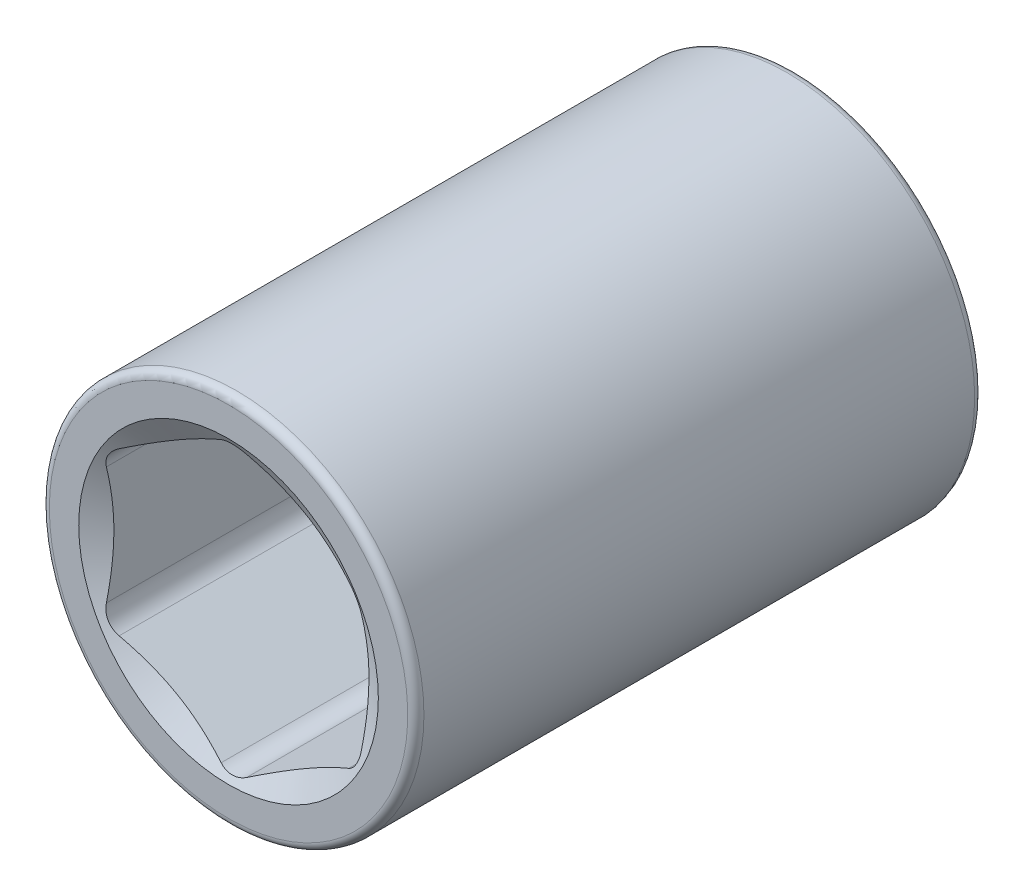
SolidWorks part; units mm, degrees
ref_plane "Front Plane" through (0, 0, 0) normal (0, 0, 1) x (1, 0, 0)
ref_plane "Top Plane" through (0, 0, 0) normal (0, 1, 0) x (1, 0, 0)
ref_plane "Right Plane" through (0, 0, 0) normal (1, 0, 0) x (0, 0, -1)
sketch "Sketch1" plane through (0, 0, 0) normal (1, 0, 0) x (0, 0, -1)
  line L0 (-11.1125, 0) -> (11.1125, 0) construction
  line L1 (11.1125, 3.175) -> (11.1125, -3.175) construction
  line L2 (-11.1125, 5) -> (-11.1125, -5) construction
  line L3 (-11.1125, 7.3422) -> (-11.1125, -7.3422) construction
  line L4 (-11.1125, 0) -> (-1.9844, 0) construction
  line L6 (11.1125, 7.3422) -> (11.1125, -7.3422) construction
  line L7 (-11.1125, 0) -> (2.7781, 0) construction
  line L9 (2.7781, 4) -> (2.7781, -4) construction
  dimension "Total Length" = 22.225
  dimension "Square Drive Size" = 6.35
  dimension "Size" = 10
  dimension "Diameter Nose End" = 14.6844
  dimension "Opening Depth" = 9.1281
  dimension "Diameter Drive End" = 14.6844
  dimension "Bolt Clearance" = 13.8906
  dimension "Bolt Clearance Diameter" = 8
sketch "Sketch4" plane through (0, 0, 0) normal (1, 0, 0) x (0, 0, -1)
  line L0 (-11.1125, 0) -> (-11.1125, 7.3422)
  line L2 (-11.1125, 7.3422) -> (11.1125, 7.3422)
  line L3 (-11.1125, 7.3422) -> (-11.1125, -7.3422) construction
  line L8 (11.1125, 3.175) -> (11.1125, -3.175) construction
  line L9 (11.1125, 7.3422) -> (11.1125, 0)
  line L11 (-11.1125, 0) -> (11.1125, 0)
revolve "Revolve1" add sketch "Sketch4" angle 360 about L11
sketch "Sketch5" plane through (0, 0, 11.1125) normal (0, 0, 1) x (1, 0, 0)
  line L27 (-5, 2.3094) -> (-5, -2.3094)
  line L28 (-4.5, -3.1754) -> (-0.5, -5.4848)
  line L29 (0.5, -5.4848) -> (4.5, -3.1754)
  line L30 (5, -2.3094) -> (5, 2.3094)
  line L31 (4.5, 3.1754) -> (0.5, 5.4848)
  line L32 (-0.5, 5.4848) -> (-4.5, 3.1754)
  circle A1 centre (0, 0) radius 5 construction
  arc A2 (-5, 2.3094) -> (-4.5, 3.1754) centre (-4, 2.3094) cw
  arc A3 (-5, -2.3094) -> (-4.5, -3.1754) centre (-4, -2.3094) ccw
  arc A4 (-0.5, -5.4848) -> (0.5, -5.4848) centre (0, -4.6188) ccw
  arc A5 (4.5, -3.1754) -> (5, -2.3094) centre (4, -2.3094) ccw
  arc A6 (5, 2.3094) -> (4.5, 3.1754) centre (4, 2.3094) ccw
  arc A7 (0.5, 5.4848) -> (-0.5, 5.4848) centre (0, 4.6188) ccw
  point P9 (0, 5.7735)
  point P21 (0, 5.7735)
  dimension "D2" = 1
  dimension "D1" = 10
extrude "Cut-Extrude1" cut sketch "Sketch5" against normal up to vertex (9.1281 mm away) up to point (0, 0, 1.9844)
sketch "Sketch7" plane through (0, 0, 1.9844) normal (0, 0, 1) x (1, 0, 0)
  circle A1 centre (0, 0) radius 4
  dimension "D1" = 8
extrude "Cut-Extrude3" cut sketch "Sketch7" against normal up to vertex (31.3974 mm away)
sketch "Sketch9" plane through (0, 0, -11.1125) normal (0, 0, -1) x (-1, 0, 0)
  line L6 (-3.175, -3.175) -> (3.175, -3.175)
  line L10 (-3.175, -3.175) -> (-3.175, 3.175)
  line L11 (-3.175, 3.175) -> (3.175, 3.175)
  line L12 (3.175, -3.175) -> (3.175, 3.175)
  line L13 (-3.175, -3.175) -> (3.175, 3.175) construction
  line L14 (-3.175, 3.175) -> (3.175, -3.175) construction
  point P0 (0, 0)
  dimension "D1" = 6.35
extrude "Cut-Extrude5" cut sketch "Sketch9" against normal up to vertex (8.3344 mm away) up to point (0, 0, -2.7781)
sketch "Sketch10" plane through (0, 0, -11.1125) normal (0, 0, -1) x (-1, 0, 0)
  line L0 (0, 0) -> (3.175, 3.175) construction
  line L1 (3.175, 3.175) -> (3.3546, 3.3546) construction
  circle A0 centre (0, 0) radius 4.7441
  dimension "D1" = 0.254
extrude "Cut-Extrude6" cut sketch "Sketch10" against normal through all draft 60
fillet "Fillet1" radius 0.3175 2 edges at (7.3422, 0, 11.1125) (7.3422, 0, -11.1125)
sketch "Sketch17" plane through (0, 0, 11.1125) normal (0, 0, 1) x (1, 0, 0)
  line L0 (0, 0) -> (0, 5.6188) construction
  line L1 (0, 5.6188) -> (0, 5.8728) construction
  circle A0 centre (0, 0) radius 5.8728
  arc A1 (0.5, 5.4848) -> (-0.5, 5.4848) centre (0, 4.6188) ccw construction
  dimension "D1" = 0.254
extrude "Cut-Extrude9" cut sketch "Sketch17" against normal through all draft 60
sketch "Sketch15" plane through (0, 0, 0) normal (1, 0, 0) x (0, 0, -1)
  line L15 (2.7781, -3.175) -> (10.9659, -3.175) construction
  line L18 (2.7781, 3.175) -> (10.9659, 3.175) construction
  line L19 (-1.9844, -4) -> (2.7781, -4) construction
  line L27 (2.7781, 4) -> (-1.9844, 4) construction
  line L29 (-10.9659, -5.6188) -> (-1.9844, -5.6188) construction
  line L31 (-1.9844, 5.6188) -> (-10.9659, 5.6188) construction
  line L32 (2.7781, -3.175) -> (10.9659, -3.175)
  line L33 (2.7781, 3.175) -> (10.9659, 3.175)
  line L34 (-1.9844, -4) -> (2.7781, -4)
  line L35 (2.7781, 4) -> (-1.9844, 4)
  line L36 (-10.9659, -5.6188) -> (-1.9844, -5.6188)
  line L38 (-1.9844, 5.6188) -> (-10.9659, 5.6188)
  line L39 (-1.9844, 5.6188) -> (-1.9844, -5.6188)
  line L40 (2.7781, 4) -> (2.7781, -4)
sketch "Sketch16" plane through (0, 0, 11.1125) normal (0, 0, 1) x (1, 0, 0)
  line L0 (-7.3422, 0) -> (7.3422, 0) construction
  dimension "D1" = 14.6844
equation "\"D1@Sketch9\" = \"Square Drive Size@Sketch1\""
equation "\"D1@Sketch16\" = \"Diameter Nose End@Sketch1\""
equation "\"D1@Sketch5\" = \"Size@Sketch1\""
equation "\"D2@Sketch5\"=\"D1@Sketch5\"*.1"
equation "\"D1@Sketch7\" = \"Bolt Clearance Diameter@Sketch1\""
